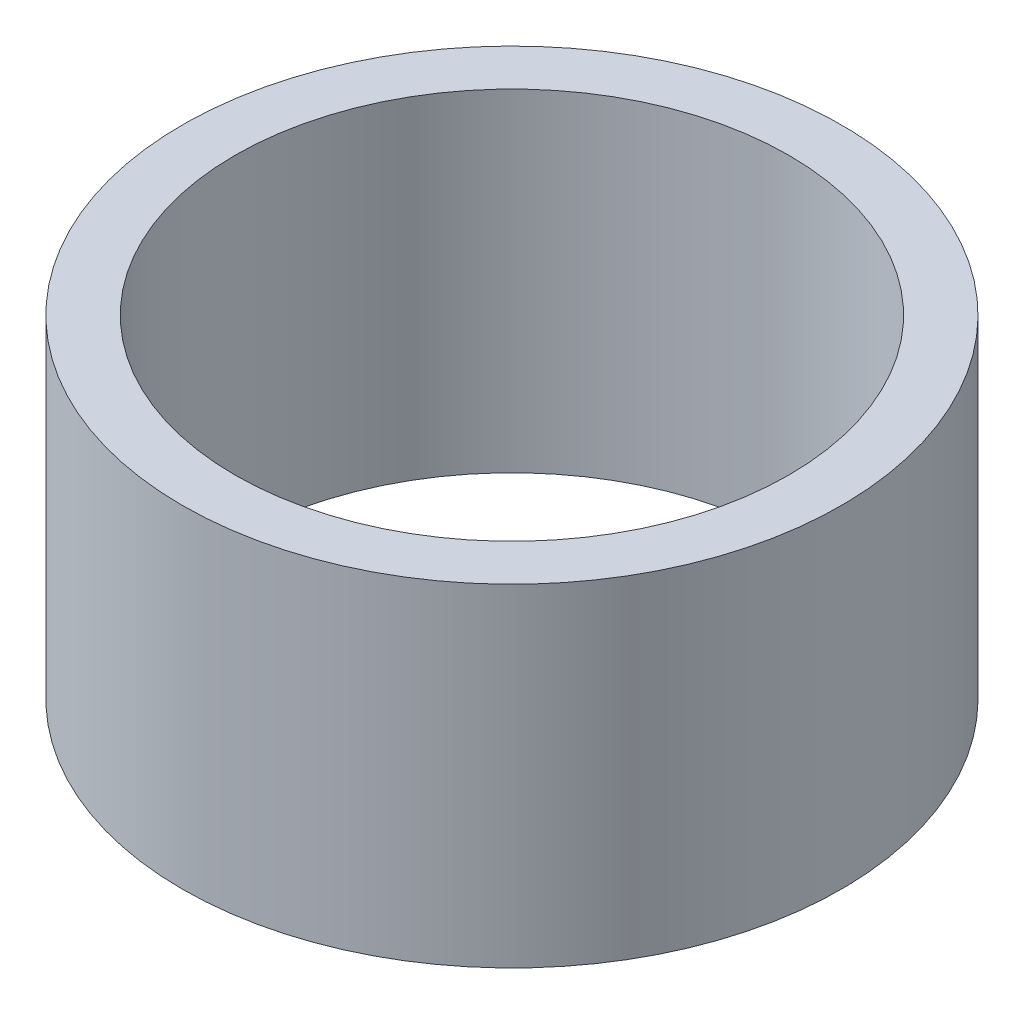
SolidWorks part; units mm, degrees
ref_plane "Front Plane" through (0, 0, 0) normal (0, 0, 1) x (1, 0, 0)
ref_plane "Top Plane" through (0, 0, 0) normal (0, 1, 0) x (1, 0, 0)
ref_plane "Right Plane" through (0, 0, 0) normal (1, 0, 0) x (0, 0, -1)
sketch "Sketch1" plane through (0, 0, 0) normal (0, 1, 0) x (1, 0, 0)
  circle A0 centre (0, 0) radius 75.565
  circle A1 centre (0, 0) radius 63.5
  dimension "D1" = 151.13
  dimension "D2" = 127
extrude "Boss-Extrude1" add sketch "Sketch1" against normal blind 76.2
